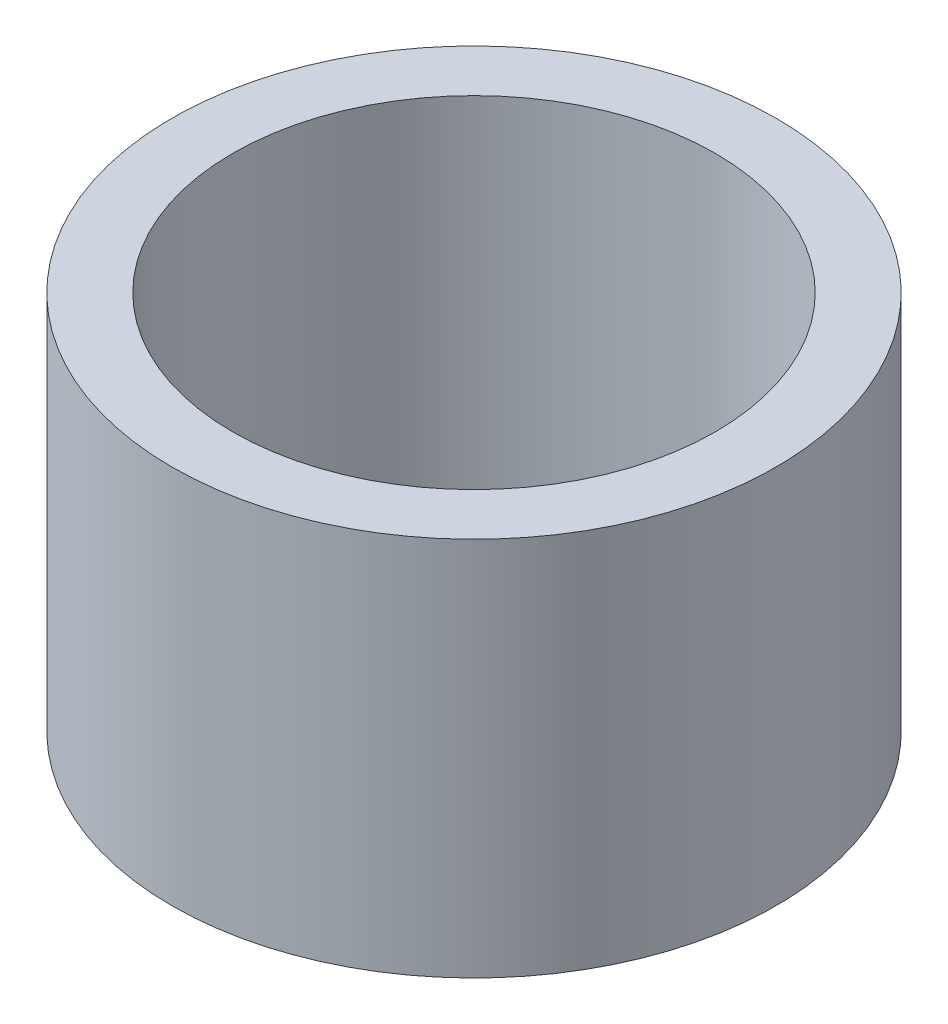
SolidWorks part; units mm, degrees
ref_plane "Front Plane" through (0, 0, 0) normal (0, 0, 1) x (1, 0, 0)
ref_plane "Top Plane" through (0, 0, 0) normal (0, 1, 0) x (1, 0, 0)
ref_plane "Right Plane" through (0, 0, 0) normal (1, 0, 0) x (0, 0, -1)
sketch "Sketch1" plane through (0, 0, 0) normal (0, 1, 0) x (1, 0, 0)
  circle A0 centre (0, 0) radius 31.75
  circle A1 centre (0, 0) radius 39.75
  dimension "D1" = 63.5
  dimension "D2" = 8
extrude "Boss-Extrude1" add sketch "Sketch1" along normal blind 50
